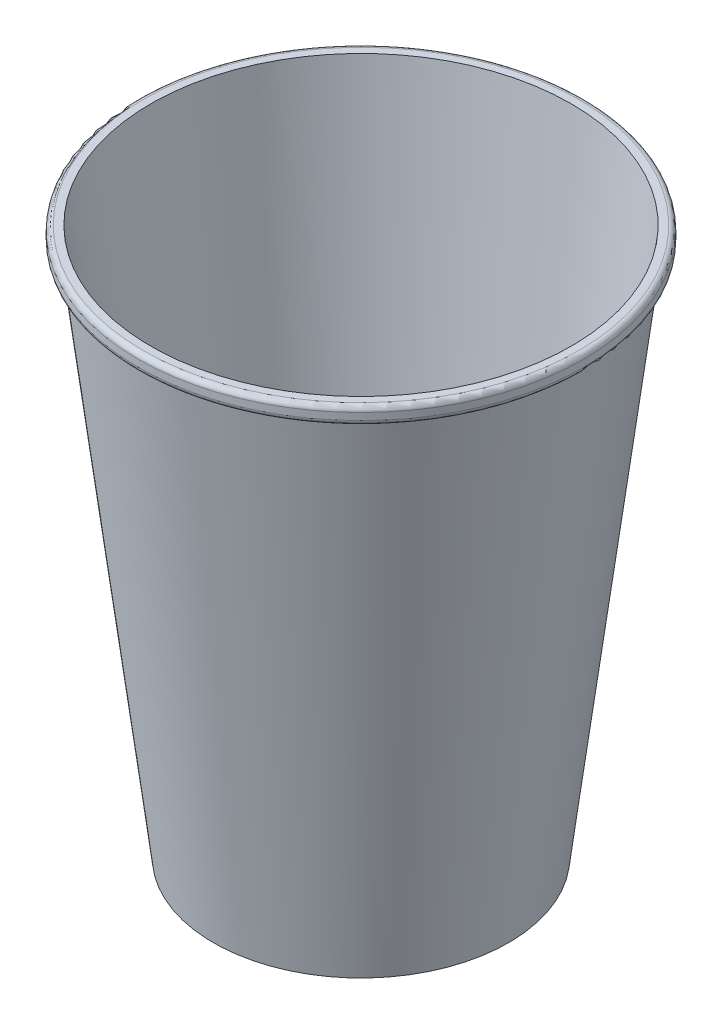
SolidWorks part; units mm, degrees
ref_plane "Alzado" through (0, 0, 0) normal (0, 0, 1) x (1, 0, 0)
ref_plane "Planta" through (0, 0, 0) normal (0, 1, 0) x (1, 0, 0)
ref_plane "Vista lateral" through (0, 0, 0) normal (1, 0, 0) x (0, 0, -1)
sketch "Croquis1" plane through (0, 0, 0) normal (0, 0, 1) x (1, 0, 0)
  line L0 (29.5076, 0) -> (42.5884, 106.1)
  line L1 (29.5076, 0) -> (28.5, 0)
  line L2 (28.5, 0) -> (29.3014, 6.5)
  line L3 (0, 0) -> (0, 7.5) construction
  line L4 (29.3014, 6.5) -> (0, 6.5)
  line L5 (0, 7.5) -> (29.4247, 7.5)
  line L6 (29.4247, 7.5) -> (42, 109.5)
  line L7 (42, 109.5) -> (44.5, 109.5)
  line L8 (42.5884, 106.1) -> (44.5, 106.1)
  line L9 (44.5, 106.1) -> (44.5, 109.5)
  line L10 (0, 7.5) -> (0, 6.5)
  line L11 (0, 7.5) -> (0, 70) construction
  line L12 (0, 70) -> (38.1377, 70) construction
  dimension "D4" = 42
  dimension "D1" = 28.5
  dimension "D2" = 1
  dimension "D3" = 6.5
  dimension "D5" = 44.5
  dimension "D6" = 3.4
  dimension "D7" = 102
  dimension "D8" = 1
  dimension "D9" = 70
  dimension "D10" = 38.1377
revolve "Revolución1" add sketch "Croquis1" angle 360 about L3
fillet "Redondeo1" radius 1 2 edges at (0, 106.1, -44.5) (0, 109.5, -44.5)
